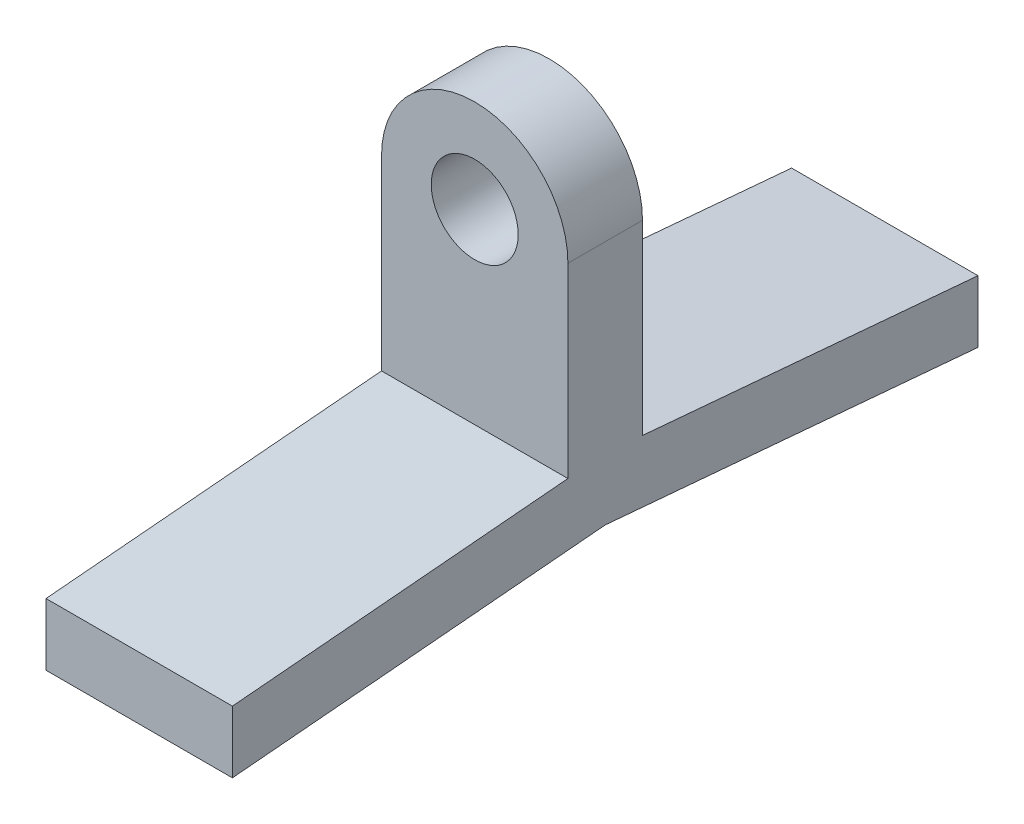
SolidWorks part; units mm, degrees
material "AISI 1045 Steel, cold drawn"
ref_plane "Ön Düzlem" through (0, 0, 0) normal (0, 0, 1) x (1, 0, 0)
ref_plane "Üst Düzlem" through (0, 0, 0) normal (0, 1, 0) x (1, 0, 0)
ref_plane "Sağ Düzlem" through (0, 0, 0) normal (1, 0, 0) x (0, 0, -1)
sketch "Sketch1" plane through (0, 0, 0) normal (0, 0, 1) x (1, 0, 0)
  line L0 (-7.5, 0) -> (-7.5, -15)
  line L1 (-7.5, -15) -> (7.5, -15)
  line L2 (7.5, -15) -> (7.5, 0)
  circle A0 centre (0, 0) radius 3.5
  arc A2 (-7.5, 0) -> (7.5, 0) centre (0, 0) cw
  dimension "D1" = 7
  dimension "D2" = 7.5
  dimension "D3" = 15
extrude "Boss-Extrude1" add sketch "Sketch1" along normal blind 6
sketch "Sketch2" plane through (7.5, 0, 0) normal (1, 0, 0) x (0, 0, -1)
  line L0 (-6, -15) -> (-33, -17.3622)
  line L1 (-33, -17.3622) -> (-33, -22.3622)
  line L2 (-33, -22.3622) -> (-3, -19.7375)
  line L3 (-6, -15) -> (0, -15)
  line L4 (-3, -19.7375) -> (27, -22.3622)
  line L5 (27, -22.3622) -> (27, -17.3622)
  line L6 (27, -17.3622) -> (0, -15)
  dimension "D1" = 170
  dimension "D2" = 5
  dimension "D3" = 60
extrude "Boss-Extrude2" add sketch "Sketch2" against normal up to surface (15 mm away) up to face at (-7.5, -7.5, 3)
